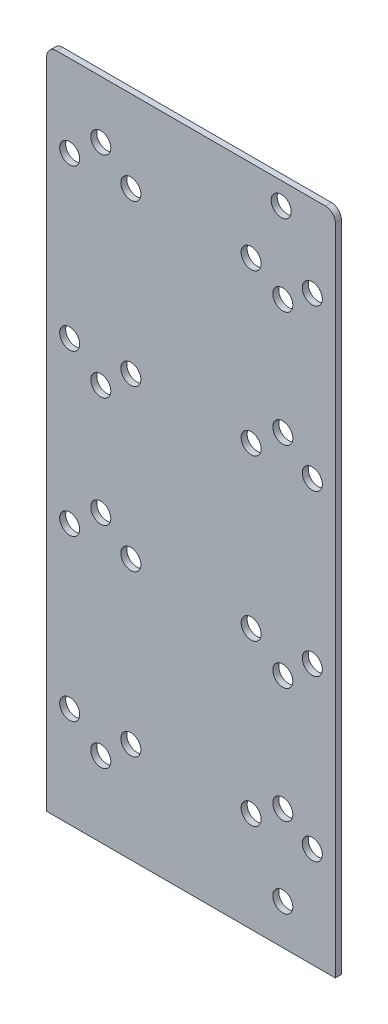
SolidWorks part; units mm, degrees
ref_plane "Front Plane" through (0, 0, 0) normal (0, 0, 1) x (1, 0, 0)
ref_plane "Top Plane" through (0, 0, 0) normal (0, 1, 0) x (1, 0, 0)
ref_plane "Right Plane" through (0, 0, 0) normal (1, 0, 0) x (0, 0, -1)
ref_plane "Plane4" through (0, 0, 3) normal (0, 0, 1) x (1, 0, 0)
sketch "Sketch1" plane through (0, 0, 3) normal (0, 0, 1) x (1, 0, 0)
  line L6 (-53.1488, 534.3974) -> (90.8512, 534.3974)
  line L7 (-53.1488, 534.3974) -> (-53.1488, 203.3974)
  line L8 (-53.1488, 203.3974) -> (90.8512, 203.3974)
  line L9 (90.8512, 534.3974) -> (90.8512, 203.3974)
  dimension "D1" = 331
  dimension "D2" = 144
extrude "Boss-Extrude1" add sketch "Sketch1" against normal blind 3
sketch "Sketch2" plane through (0, 0, 3) normal (0, 0, 1) x (1, 0, 0)
  line L0 (90.8512, 534.3974) -> (-53.1488, 534.3974) construction
  line L1 (90.8512, 203.3974) -> (90.8512, 534.3974) construction
  line L2 (-53.1488, 203.3974) -> (90.8512, 203.3974) construction
  circle A0 centre (63.8512, 523.3974) radius 5
  circle A1 centre (64.6359, 483.3974) radius 5
  circle A2 centre (64.6359, 425.8974) radius 5
  circle A3 centre (64.6359, 320.8974) radius 5
  circle A4 centre (64.6359, 263.3974) radius 5
  circle A5 centre (64.6359, 223.3974) radius 5
  dimension "D1" = 10
  dimension "D2" = 11
  dimension "D3" = 27
  dimension "D4" = 20
  dimension "D5" = 60
  dimension "D6" = 117.5
  dimension "D7" = 222.5
  dimension "D8" = 280
extrude "Cut-Extrude1" cut sketch "Sketch2" against normal through all
sketch "Sketch3" plane through (0, 0, 3) normal (0, 0, 1) x (1, 0, 0)
  line L0 (-53.1488, 203.3974) -> (90.8512, 203.3974) construction
  line L1 (-26.1488, 505.8974) -> (-26.1488, 400.8974) construction
  line L2 (-26.1488, 400.8974) -> (-26.1488, 345.8974) construction
  line L3 (-26.1488, 345.8974) -> (-26.1488, 240.8974) construction
  line L4 (-53.1488, 534.3974) -> (-53.1488, 203.3974) construction
  circle A0 centre (-26.1488, 505.8974) radius 5
  circle A1 centre (-26.1488, 400.8974) radius 5
  circle A2 centre (-26.1488, 345.8974) radius 5
  circle A3 centre (-26.1488, 240.8974) radius 5
  dimension "D5" = 10
  dimension "D1" = 37.5
  dimension "D2" = 142.5
  dimension "D3" = 197.5
  dimension "D4" = 302.5
  dimension "D6" = 27
extrude "Cut-Extrude2" cut sketch "Sketch3" against normal blind 10
sketch "Sketch4" plane through (0, 0, 3) normal (0, 0, 1) x (1, 0, 0)
  line L0 (79.3512, 253.3974) -> (48.8512, 253.3974) construction
  line L1 (48.8512, 253.3974) -> (-11.1488, 253.3974) construction
  line L2 (-11.1488, 253.3974) -> (-41.6488, 253.3974) construction
  line L3 (-53.1488, 203.3974) -> (90.8512, 203.3974) construction
  circle A0 centre (-41.6488, 253.3974) radius 5
  circle A1 centre (-11.1488, 253.3974) radius 5
  circle A2 centre (48.8512, 253.3974) radius 5
  circle A3 centre (79.3512, 253.3974) radius 5
  point P10 (18.8512, 253.3974)
  point P11 (18.8512, 203.3974)
  dimension "D1" = 10
  dimension "D2" = 30.5
  dimension "D3" = 30.5
  dimension "D4" = 60
  dimension "D5" = 50
extrude "Cut-Extrude3" cut sketch "Sketch4" against normal blind 10
pattern_linear "LPattern1" count 4 spacing 80 along (0, 1, 0) of "Cut-Extrude3"
fillet "Fillet1" radius 5 2 edges at (90.8512, 534.3974, 1.5) (-53.1488, 534.3974, 1.5)
